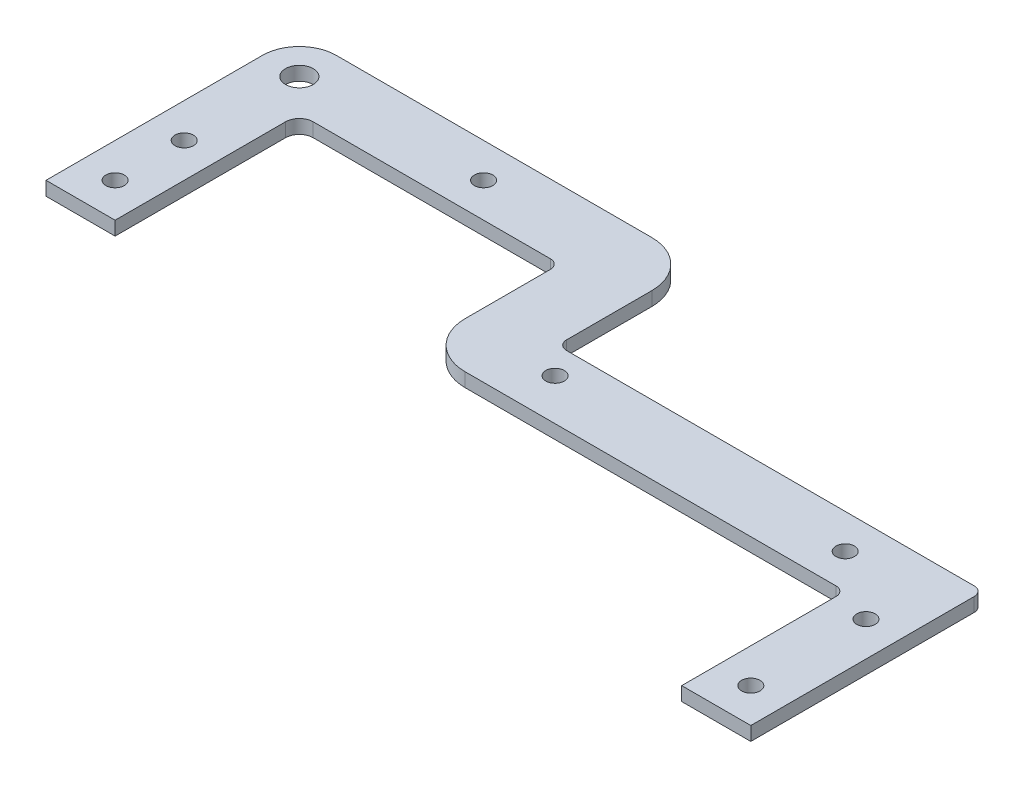
SolidWorks part; units mm, degrees
material "Thornel Mat VMA"
ref_plane "前视基准面" through (0, 0, 0) normal (0, 0, 1) x (1, 0, 0)
ref_plane "上视基准面" through (0, 0, 0) normal (0, 1, 0) x (1, 0, 0)
ref_plane "右视基准面" through (0, 0, 0) normal (1, 0, 0) x (0, 0, -1)
sketch "草图1" plane through (0, 0, 0) normal (0, 1, 0) x (1, 0, 0)
  line L1 (-55, 0) -> (-40, 0)
  line L12 (-204, 66) -> (-147.5, 66)
  line L28 (-211, 81) -> (-132.5, 81)
  line L31 (-147.5, 66) -> (-147.5, 35.5)
  line L37 (-219, 73) -> (-219, 26)
  line L39 (0, 0) -> (0, 76.5) construction
  line L64 (-132.5, 50.5) -> (-132.5, 81)
  line L66 (-219, 26) -> (-204, 26)
  line L68 (-204, 26) -> (-204, 66)
  line L70 (-55, 0) -> (-55, 35.5)
  line L74 (-40, 0) -> (-40, 50.5)
  line L80 (-147.5, 35.5) -> (-55, 35.5)
  line L82 (-132.5, 50.5) -> (-40, 50.5)
  arc A0 (-211, 81) -> (-219, 73) centre (-211, 73) ccw
  dimension "D3" = 92.5
  dimension "D4" = 81
  dimension "D5" = 179
  dimension "D6" = 15
  dimension "D7" = 8
  dimension "D10" = 15
  dimension "D12" = 15
  dimension "D8" = 40
  dimension "D13" = 50.5
  dimension "D17" = 55
  dimension "D19" = 15
  dimension "D22" = 15
extrude "凸台-拉伸1" add sketch "草图1" along normal blind 3
sketch "草图2" plane through (0, 3, 0) normal (0, 1, 0) x (1, 0, 0)
  line L0 (-132.5, 81) -> (-211, 81) construction
  line L1 (-55, 0) -> (-40, 0) construction
  line L3 (-47.5, 32.5) -> (-47.5, 0) construction
  line L6 (-219, 73) -> (-219, 26) construction
  line L7 (-219, 26) -> (-204, 26) construction
  line L8 (-40, 50.5) -> (-132.5, 50.5) construction
  line L11 (-132.5, 50.5) -> (-132.5, 81) construction
  line L14 (-55, 35.5) -> (-55, 0) construction
  circle A10 centre (-47.5, 32.5) radius 2
  circle A18 centre (-211.5, 33.5) radius 2
  circle A19 centre (-211.5, 48.5) radius 2
  circle A39 centre (-211, 73) radius 3
  circle A41 centre (-171.5, 73.5) radius 2
  circle A42 centre (-127, 44.5) radius 2
  circle A47 centre (-62.5, 43) radius 2
  circle A48 centre (-47.5, 7.5) radius 2
  point P29 (-211.5, 26)
  dimension "D3" = 25
  dimension "D4" = 8
  dimension "D7" = 15
  dimension "D8" = 7.5
  dimension "D9" = 4
  dimension "D10" = 7.5
  dimension "D11" = 47.5
  dimension "D6" = 7.5
  dimension "D19" = 4
  dimension "D23" = 7.5
  dimension "D13" = 6
  dimension "D14" = 5.5
  dimension "D15" = 6
  dimension "D5" = 7.5
  dimension "D12" = 8
extrude "切除-拉伸1" cut sketch "草图2" against normal blind 10
fillet "圆角1" radius 10 2 edges at (-132.5, 1.5, -81) (-147.5, 1.5, -35.5)
fillet "圆角2" radius 2 4 edges at (-40, 1.5, -50.5) (-55, 1.5, -35.5) (-147.5, 1.5, -66) (-132.5, 1.5, -50.5)
fillet "圆角3" radius 3 1 edges at (-204, 1.5, -66)
